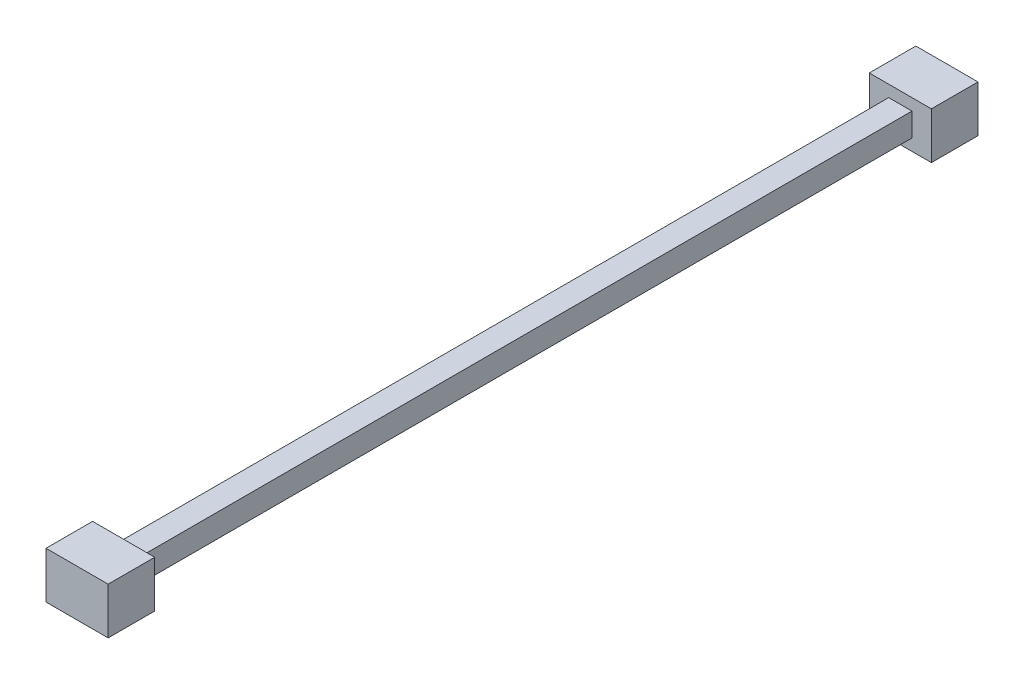
SolidWorks part; units mm, degrees
ref_plane "前视基准面" through (0, 0, 0) normal (0, 0, 1) x (1, 0, 0)
ref_plane "上视基准面" through (0, 0, 0) normal (0, 1, 0) x (1, 0, 0)
ref_plane "右视基准面" through (0, 0, 0) normal (1, 0, 0) x (0, 0, -1)
sketch "草图1" plane through (0, 0, 0) normal (0, 0, 1) x (1, 0, 0)
  line L1 (-7.5, -7.5) -> (7.5, -7.5)
  line L2 (-7.5, -7.5) -> (-7.5, 7.5)
  line L3 (-7.5, 7.5) -> (7.5, 7.5)
  line L4 (7.5, -7.5) -> (7.5, 7.5)
  line L5 (-7.5, -7.5) -> (7.5, 7.5) construction
  line L6 (-7.5, 7.5) -> (7.5, -7.5) construction
  point P0 (0, 0)
extrude "凸台-拉伸1" add sketch "草图1" along normal blind 500
sketch "草图2" plane through (0, 0, 500) normal (0, 0, 1) x (1, 0, 0)
  line L1 (-20, -15) -> (20, -15)
  line L2 (-20, -15) -> (-20, 15)
  line L3 (-20, 15) -> (20, 15)
  line L4 (20, -15) -> (20, 15)
  line L5 (-20, -15) -> (20, 15) construction
  line L6 (-20, 15) -> (20, -15) construction
  point P0 (0, 0)
extrude "凸台-拉伸2" add sketch "草图2" along normal blind 30
sketch "草图3" plane through (0, 0, 0) normal (0, 0, -1) x (-1, 0, 0)
  line L1 (-20, 15) -> (20, 15)
  line L2 (-20, 15) -> (-20, -15)
  line L3 (-20, -15) -> (20, -15)
  line L4 (20, 15) -> (20, -15)
  line L5 (-20, 15) -> (20, -15) construction
  line L6 (-20, -15) -> (20, 15) construction
  point P0 (0, 0)
extrude "凸台-拉伸3" add sketch "草图3" along normal blind 30
